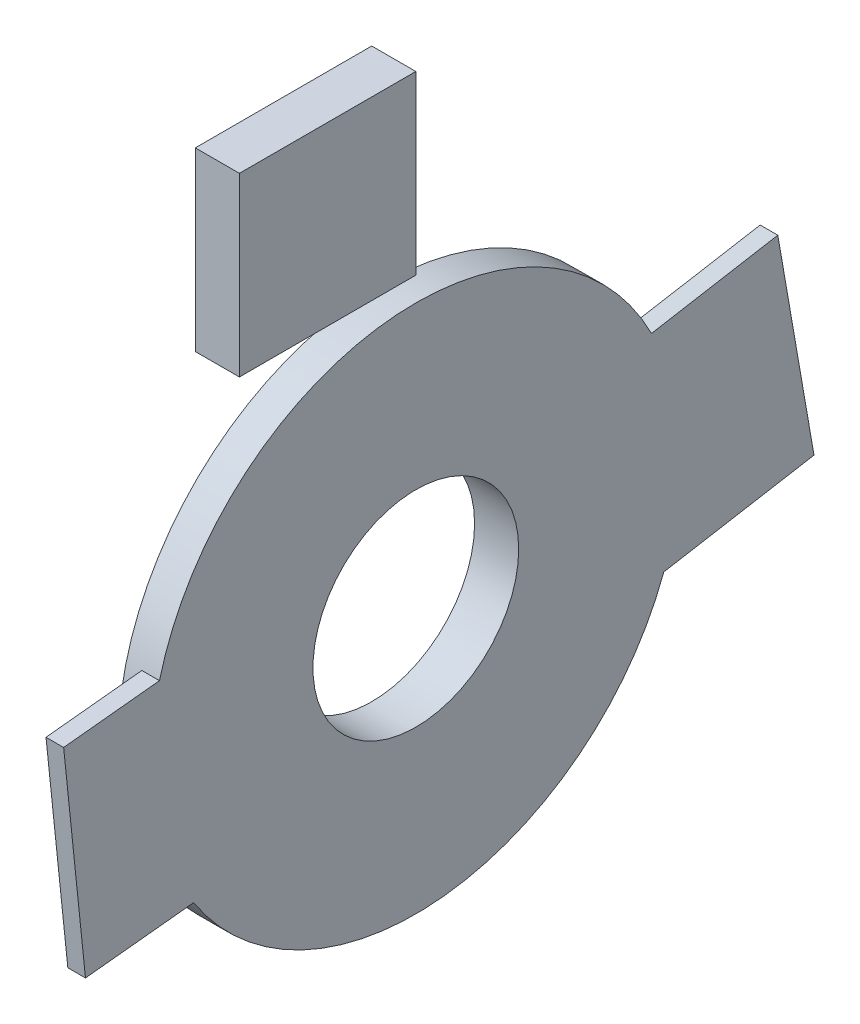
SolidWorks part; units mm, degrees
material "6061-T6 (SS)"
ref_plane "Front Plane" through (0, 0, 0) normal (0, 0, 1) x (1, 0, 0)
ref_plane "Top Plane" through (0, 0, 0) normal (0, 1, 0) x (1, 0, 0)
ref_plane "Right Plane" through (0, 0, 0) normal (1, 0, 0) x (0, 0, -1)
sketch "Sketch1" plane through (0, 0, 0) normal (1, 0, 0) x (0, 0, -1)
  line L1 (3.7028, 6.4135) -> (-3.7028, 6.4135) construction
  line L2 (-3.7028, 6.4135) -> (-7.4057, 0) construction
  line L3 (-7.4057, 0) -> (-3.7028, -6.4135) construction
  line L4 (-3.7028, -6.4135) -> (3.7028, -6.4135) construction
  line L5 (3.7028, -6.4135) -> (7.4057, 0) construction
  line L6 (7.4057, 0) -> (3.7028, 6.4135) construction
  circle A0 centre (0, 0) radius 7.4057
  circle A2 centre (0, 0) radius 19.05
  circle A3 centre (0, 0) radius 6.4135 construction
  dimension "D1" = 12.827
  dimension "D2" = 38.1
extrude "Boss-Extrude1" add sketch "Sketch1" along normal blind 3.175
sketch "Sketch3" plane through (0, 0, 0) normal (0, 0, 1) x (1, 0, 0)
  line L0 (0, 19.05) -> (0, -19.05) construction
  line L1 (0, 19.05) -> (0.7874, 19.05)
  line L2 (0, 19.05) -> (0, 9.525)
  line L3 (0, 9.525) -> (0.7874, 9.525)
  line L4 (0.7874, 19.05) -> (0.7874, 9.525)
  line L5 (0, 0) -> (3.175, 0) construction
  line L6 (3.175, -19.05) -> (3.175, 19.05) construction
  line L7 (3.175, 19.05) -> (0, 19.05) construction
  dimension "D1" = 19.05
  dimension "D2" = 0.7874
revolve "Cut-Revolve1" cut sketch "Sketch3" angle 360 about L5
sketch "Sketch4" plane through (3.175, 0, 0) normal (1, 0, 0) x (0, 0, -1)
  line L0 (0, 20.7764) -> (0, 33.4764)
  line L1 (0, 20.7764) -> (-12.7, 20.7764)
  line L2 (0, 33.4764) -> (-12.7, 33.4764)
  line L3 (-12.7, 20.7764) -> (-12.7, 33.4764)
  dimension "D1" = 12.7
extrude "Boss-Extrude2" add sketch "Sketch4" against normal up to surface (3.175 mm away) separate body up to face at (0, 0, -7.4057)
sketch "Sketch5" plane through (3.175, 0, 0) normal (1, 0, 0) x (0, 0, -1)
  line L0 (12.6032, 7.907) -> (15.2079, -7.1088)
  line L1 (12.6032, 7.907) -> (26.0584, 10.241)
  line L2 (15.2079, -7.1088) -> (28.6631, -4.7748)
  line L3 (26.0584, 10.241) -> (28.6631, -4.7748)
  line L4 (-14.9134, 5.0917) -> (-13.3416, -10.067)
  line L5 (-14.9134, 5.0917) -> (-25.3528, 4.0093)
  line L6 (-13.3416, -10.067) -> (-23.781, -11.1494)
  line L7 (-25.3528, 4.0093) -> (-23.781, -11.1494)
  dimension "D1" = 15.24
extrude "Boss-Extrude3" add sketch "Sketch5" against normal blind 1.27
sketch "Sketch6" plane through (0, 0, 0) normal (-1, 0, 0) x (0, 0, 1)
  circle A0 centre (0, 0) radius 9.525
  circle A1 centre (0, 0) radius 19.05
  circle A2 centre (0, 0) radius 19.05 construction
  circle A3 centre (0, 0) radius 9.525 construction
